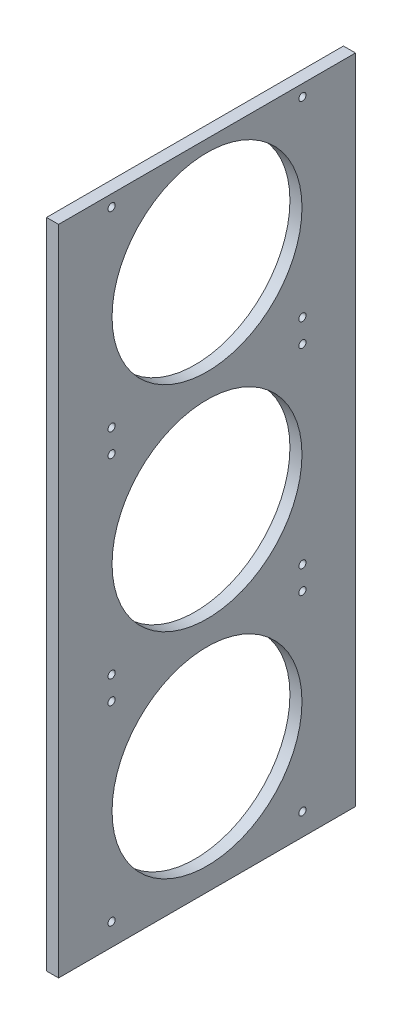
SolidWorks part; units mm, degrees
ref_plane "Front Plane" through (0, 0, 0) normal (0, 0, 1) x (1, 0, 0)
ref_plane "Top Plane" through (0, 0, 0) normal (0, 1, 0) x (1, 0, 0)
ref_plane "Right Plane" through (0, 0, 0) normal (1, 0, 0) x (0, 0, -1)
sketch "Sketch1" plane through (0, 0, 0) normal (0, 1, 0) x (1, 0, 0)
  line L1 (-83.25, 55.5) -> (83.25, 55.5)
  line L2 (-83.25, 55.5) -> (-83.25, -55.5)
  line L3 (-83.25, -55.5) -> (83.25, -55.5)
  line L4 (83.25, 55.5) -> (83.25, -55.5)
  line L5 (-83.25, 55.5) -> (83.25, -55.5) construction
  line L6 (-83.25, -55.5) -> (83.25, 55.5) construction
  point P0 (0, 0)
  dimension "D1" = 166.5
  dimension "D2" = 111
extrude "Boss-Extrude1" add sketch "Sketch1" along normal blind 30.5
shell "Shell1" thickness 4.5
sketch "Sketch2" plane through (0, 4.5, 0) normal (0, 1, 0) x (1, 0, 0)
  line L5 (78.75, 51) -> (-83.25, 51) construction
  line L6 (-78.25, 46) -> (78.75, 46)
  line L9 (-78.25, 46) -> (-78.25, -46)
  line L10 (-78.25, -46) -> (78.75, -46)
  line L11 (78.75, 46) -> (78.75, -46)
  line L12 (-83.25, -51) -> (78.75, -51) construction
  line L13 (-83.25, 51) -> (-83.25, -51) construction
  line L14 (78.75, -51) -> (78.75, 51) construction
  point P0 (0, 0)
  dimension "D1" = 5
  dimension "D2" = 5
  dimension "D3" = 5
extrude "Cut-Extrude1" cut sketch "Sketch2" against normal up to next
hole_wizard "Tap Drill for #6-32 Tap1" positions "Sketch4" profile "Sketch5" hole size "#6-32" standard "ANSI Inch"
sketch "Sketch4" plane through (0, 0, -55.5) normal (0, 0, -1) x (-1, 0, 0)
  line L0 (-78.75, 4.5) -> (83.25, 4.5) construction
  line L2 (-78.75, 30.5) -> (-78.75, 4.5) construction
  point P0 (42.66, 10.84)
  point P2 (-58.75, 10.84)
  dimension "D1" = 6.34
  dimension "D2" = 20
  dimension "D3" = 101.41
sketch "Sketch5" plane through (-42.66, 10.84, -55.5) normal (1, 0, 0) x (0, 1, 0)
  line L0 (0, 0) -> (0, 4.5)
  line L1 (0, 4.5) -> (1.3525, 4.5)
  line L2 (1.3525, 4.5) -> (1.3525, 0)
  line L5 (1.3525, 0) -> (0, 0)
  line L11 (0, -6.35) -> (0, 107.95) construction
  dimension "Thru Hole Dia." = 2.7051
  dimension "Thru Hole Depth" = 4.5
mirror "Mirror1" about plane through (0, 0, 0) normal (0, 0, 1) of "Tap Drill for #6-32 Tap1"
pattern_linear "LPattern1" count 8 spacing 30.5 along (0, 1, 0) of bodies 104
combine bodies "Combine1" operation type add bodies to combine 104 105
sketch "Sketch7" plane through (-83.25, 0, 0) normal (-1, 0, 0) x (0, 0, 1)
  line L1 (-51, 30.5) -> (51, 30.5)
  line L2 (-51, 30.5) -> (-51, 35)
  line L3 (-51, 35) -> (51, 35)
  line L4 (51, 30.5) -> (51, 35)
extrude "Cut-Extrude2" cut sketch "Sketch7" against normal up to surface (5 mm away) up to face at (-78.25, 32.75, 0)
combine bodies "Combine2" operation type add bodies to combine 109 110 112 111 114 108 113
sketch "Sketch8" plane through (-83.25, 0, 0) normal (-1, 0, 0) x (0, 0, 1)
  line L1 (-51, 61) -> (51, 61)
  line L2 (-51, 61) -> (-51, 218)
  line L3 (-51, 218) -> (51, 218)
  line L4 (51, 61) -> (51, 218)
extrude "Cut-Extrude3" cut sketch "Sketch8" against normal up to surface (5 mm away) up to face at (-78.25, 215.75, 0)
sketch "Sketch9" plane through (83.25, 0, 0) normal (1, 0, 0) x (0, 0, -1)
  line L0 (-55.5, 244) -> (55.5, 244) construction
  line L1 (-40, 244) -> (40, 244) construction
  line L2 (-40, 244) -> (-40, 4) construction
  line L3 (-40, 4) -> (40, 4) construction
  line L4 (40, 244) -> (40, 4) construction
  line L5 (0, 244) -> (0, 4) construction
  line L6 (-40, 164) -> (40, 164) construction
  line L7 (-40, 84) -> (40, 84) construction
  circle A0 centre (0, 204) radius 35.5
  circle A1 centre (0, 124) radius 35.5
  circle A2 centre (0, 44) radius 35.5
  dimension "D5" = 71
  dimension "D7" = 71
  dimension "D8" = 71
  dimension "D1" = 240
  dimension "D2" = 80
  dimension "D3" = 80
  dimension "D4" = 80
  dimension "D6" = 40
  dimension "D9" = 40
extrude "Cut-Extrude4" cut sketch "Sketch9" against normal up to next
sketch "Sketch10" plane through (83.25, 0, 0) normal (1, 0, 0) x (0, 0, -1)
  line L0 (0, 239.5) -> (0, 168.5) construction
  line L1 (-40, 204) -> (40, 204) construction
  line L2 (-40, 244) -> (40, 244) construction
  line L3 (-40, 244) -> (-40, 164) construction
  line L4 (-40, 164) -> (40, 164) construction
  line L5 (40, 244) -> (40, 164) construction
  line L6 (-40, 244) -> (40, 164) construction
  line L7 (-40, 164) -> (40, 244) construction
  circle A0 centre (0, 204) radius 35.5 construction
  circle A1 centre (-35.675, 239.675) radius 2.175
  circle A2 centre (35.675, 239.675) radius 2.175
  circle A3 centre (35.675, 168.325) radius 2.175
  circle A4 centre (-35.675, 168.325) radius 2.175
  point P5 (0, 204)
  dimension "D2" = 80
  dimension "D3" = 4.35
  dimension "D1" = 80
  dimension "D4" = 4.325
hole_wizard "Tap Drill for #6-32 Tap2" positions "Sketch11" profile "Sketch12" hole size "#6-32" standard "ANSI Inch" end condition up to next
sketch "Sketch11" plane through (83.25, 0, 0) normal (1, 0, 0) x (0, 0, -1)
  point P0 (-35.675, 239.675)
  point P3 (35.675, 239.675)
  point P6 (35.675, 168.325)
  point P9 (-35.675, 168.325)
sketch "Sketch12" plane through (83.25, 239.675, 35.675) normal (0, 1, 0) x (0, 0, -1)
  line L0 (0, 0) -> (0, 4.5)
  line L1 (0, 4.5) -> (1.3525, 4.5)
  line L2 (1.3525, 4.5) -> (1.3525, 0)
  line L5 (1.3525, 0) -> (0, 0)
  line L11 (0, -6.35) -> (0, 107.95) construction
  dimension "Thru Hole Dia." = 2.7051
  dimension "Thru Hole Depth" = 4.5
ref_plane "Plane1" through (0, 164, 0) normal (0, 1, 0) x (1, 0, 0)
mirror "Mirror2" about plane through (0, 164, 0) normal (0, 1, 0) of "Tap Drill for #6-32 Tap2"
ref_plane "Plane2" through (0, 124, 0) normal (0, 1, 0) x (1, 0, 0)
mirror "Mirror3" about plane through (0, 124, 0) normal (0, 1, 0) of "Tap Drill for #6-32 Tap2"
sketch "Sketch14" plane through (-83.25, 0, 0) normal (-1, 0, 0) x (0, 0, 1)
  line L1 (-55.5, 0) -> (55.5, 0)
  line L2 (-55.5, 0) -> (-55.5, 244)
  line L3 (-55.5, 244) -> (55.5, 244)
  line L4 (55.5, 0) -> (55.5, 244)
extrude "Cut-Extrude6" cut sketch "Sketch14" against normal up to surface (162 mm away)
equation "\"Drive Lenght\" = 162"
equation "\"Drive Width\"= 102"
equation "\"Drive Thickness\"= 25.5"
equation "\"D1@Sketch1\"=\"Drive Lenght\"+\"Spacer\""
equation "\"D2@Sketch1\"=\"Drive Width\" +\"Spacer\"*2"
equation "\"D1@Boss-Extrude1\"=\"Drive Thickness\"+5"
equation "\"D1@Sketch2\"=5"
equation "\"D2@Sketch2\"=5"
equation "\"D3@Sketch2\"=5"
equation "\"Spacer\" = 4.5"
equation "\"Drive Hole from botton\" = 6.34"
equation "\"Between Drive holes\"= 101.41"
equation "\"Drive hole to fron\"= 20"
equation "\"D1@Sketch4\"=\"Drive Hole from botton\""
equation "\"D2@Sketch4\"=\"Drive hole to fron\""
equation "\"D3@Sketch4\"=\"Between Drive holes\""
equation "\"D3@LPattern1\"=\"Drive Thickness\"+5 "
equation "\"D6@Sketch9\"=40"
equation "\"D7@Sketch9\"=\"D5@Sketch9\""
equation "\"D8@Sketch9\"=\"D5@Sketch9\""
equation "\"D2@Sketch10\"=\"D1@Sketch10\""
